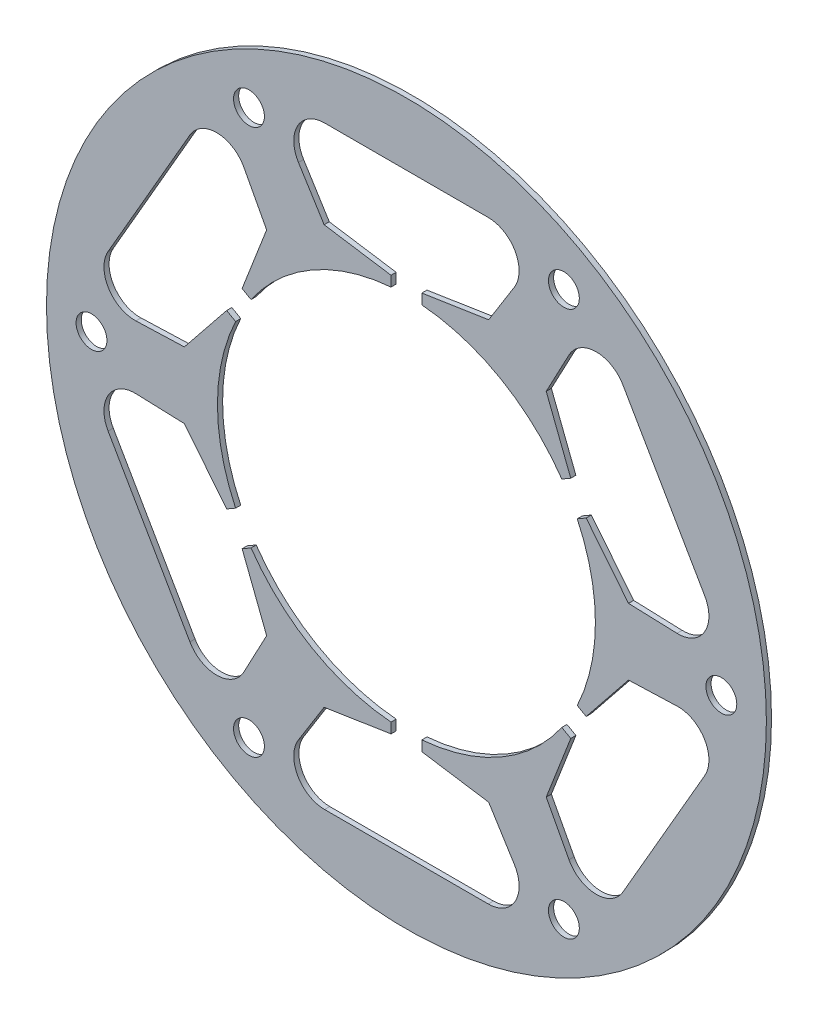
SolidWorks part; units mm, degrees
ref_plane "Ön Düzlem" through (0, 0, 0) normal (0, 0, 1) x (1, 0, 0)
ref_plane "Üst Düzlem" through (0, 0, 0) normal (0, 1, 0) x (1, 0, 0)
ref_plane "Sağ Düzlem" through (0, 0, 0) normal (1, 0, 0) x (0, 0, -1)
sketch "Çizim2" plane through (0, 0, 0) normal (0, 0, 1) x (1, 0, 0)
  line L0 (-15.1101, 10.4559) -> (-15.9761, 10.9559)
  line L1 (-1.5, 19.3137) -> (-1.5, 18.3137)
  line L2 (-8, 20.3137) -> (-1.5, 19.3137)
  line L3 (-10.5, 24.3137) -> (-8, 20.3137)
  line L4 (7.956, 28.9037) -> (-7.956, 28.9037)
  line L5 (8, 20.3137) -> (10.5, 24.3137)
  line L6 (1.5, 19.3137) -> (8, 20.3137)
  line L7 (1.5, 18.3137) -> (1.5, 19.3137)
  line L8 (15.9761, 10.9559) -> (15.1101, 10.4559)
  line L9 (13.5922, 17.085) -> (15.9761, 10.9559)
  line L10 (15.8063, 21.2501) -> (13.5922, 17.085)
  line L11 (29.0093, 7.5617) -> (21.0533, 21.3419)
  line L12 (21.5922, 3.2286) -> (26.3063, 3.0636)
  line L13 (17.4761, 8.3578) -> (21.5922, 3.2286)
  line L14 (16.6101, 7.8578) -> (17.4761, 8.3578)
  line L15 (17.4761, -8.3578) -> (16.6101, -7.8578)
  line L16 (21.5922, -3.2286) -> (17.4761, -8.3578)
  line L17 (26.3063, -3.0636) -> (21.5922, -3.2286)
  line L18 (21.0533, -21.3419) -> (29.0093, -7.5617)
  line L19 (13.5922, -17.085) -> (15.8063, -21.2501)
  line L20 (15.9761, -10.9559) -> (13.5922, -17.085)
  line L21 (15.1101, -10.4559) -> (15.9761, -10.9559)
  line L22 (1.5, -19.3137) -> (1.5, -18.3137)
  line L23 (8, -20.3137) -> (1.5, -19.3137)
  line L24 (10.5, -24.3137) -> (8, -20.3137)
  line L25 (-7.956, -28.9037) -> (7.956, -28.9037)
  line L26 (-8, -20.3137) -> (-10.5, -24.3137)
  line L27 (-1.5, -19.3137) -> (-8, -20.3137)
  line L28 (-1.5, -18.3137) -> (-1.5, -19.3137)
  line L29 (-15.9761, -10.9559) -> (-15.1101, -10.4559)
  line L30 (-13.5922, -17.085) -> (-15.9761, -10.9559)
  line L31 (-15.8063, -21.2501) -> (-13.5922, -17.085)
  line L32 (-29.0093, -7.5617) -> (-21.0533, -21.3419)
  line L33 (-21.5922, -3.2286) -> (-26.3063, -3.0636)
  line L34 (-17.4761, -8.3578) -> (-21.5922, -3.2286)
  line L35 (-16.6101, -7.8578) -> (-17.4761, -8.3578)
  line L36 (-17.4761, 8.3578) -> (-16.6101, 7.8578)
  line L37 (-21.5922, 3.2286) -> (-17.4761, 8.3578)
  line L38 (-26.3063, 3.0636) -> (-21.5922, 3.2286)
  line L39 (-21.0533, 21.3419) -> (-29.0093, 7.5617)
  line L40 (-13.5922, 17.085) -> (-15.8063, 21.2501)
  line L41 (-15.9761, 10.9559) -> (-13.5922, 17.085)
  circle A0 centre (-15.3101, -26.5179) radius 1.5
  circle A1 centre (30.6203, 0) radius 1.5
  circle A2 centre (-15.3101, 26.5179) radius 1.5
  circle A3 centre (0, 0) radius 35
  arc A4 (-1.5, 18.3137) -> (-15.1101, 10.4559) centre (0, 0) ccw
  arc A5 (-7.956, 28.9037) -> (-10.5, 24.3137) centre (-7.956, 25.9037) ccw
  arc A6 (10.5, 24.3137) -> (7.956, 28.9037) centre (7.956, 25.9037) ccw
  arc A7 (15.1101, 10.4559) -> (1.5, 18.3137) centre (0, 0) ccw
  arc A8 (21.0533, 21.3419) -> (15.8063, 21.2501) centre (18.4552, 19.8419) ccw
  arc A9 (26.3063, 3.0636) -> (29.0093, 7.5617) centre (26.4112, 6.0617) ccw
  arc A10 (16.6101, -7.8578) -> (16.6101, 7.8578) centre (0, 0) ccw
  arc A11 (29.0093, -7.5617) -> (26.3063, -3.0636) centre (26.4112, -6.0617) ccw
  arc A12 (15.8063, -21.2501) -> (21.0533, -21.3419) centre (18.4552, -19.8419) ccw
  arc A13 (1.5, -18.3137) -> (15.1101, -10.4559) centre (0, 0) ccw
  arc A14 (7.956, -28.9037) -> (10.5, -24.3137) centre (7.956, -25.9037) ccw
  arc A15 (-10.5, -24.3137) -> (-7.956, -28.9037) centre (-7.956, -25.9037) ccw
  arc A16 (-15.1101, -10.4559) -> (-1.5, -18.3137) centre (0, 0) ccw
  arc A17 (-21.0533, -21.3419) -> (-15.8063, -21.2501) centre (-18.4552, -19.8419) ccw
  arc A18 (-26.3063, -3.0636) -> (-29.0093, -7.5617) centre (-26.4112, -6.0617) ccw
  arc A19 (-16.6101, 7.8578) -> (-16.6101, -7.8578) centre (0, 0) ccw
  arc A20 (-29.0093, 7.5617) -> (-26.3063, 3.0636) centre (-26.4112, 6.0617) ccw
  arc A21 (-15.8063, 21.2501) -> (-21.0533, 21.3419) centre (-18.4552, 19.8419) ccw
  circle A22 centre (15.3101, 26.5179) radius 1.5
  circle A23 centre (15.3101, -26.5179) radius 1.5
  circle A24 centre (-30.6203, 0) radius 1.5
extrude "Yükseklik-Ekstrüzyon1" add sketch "Çizim2" along normal blind 0.5
